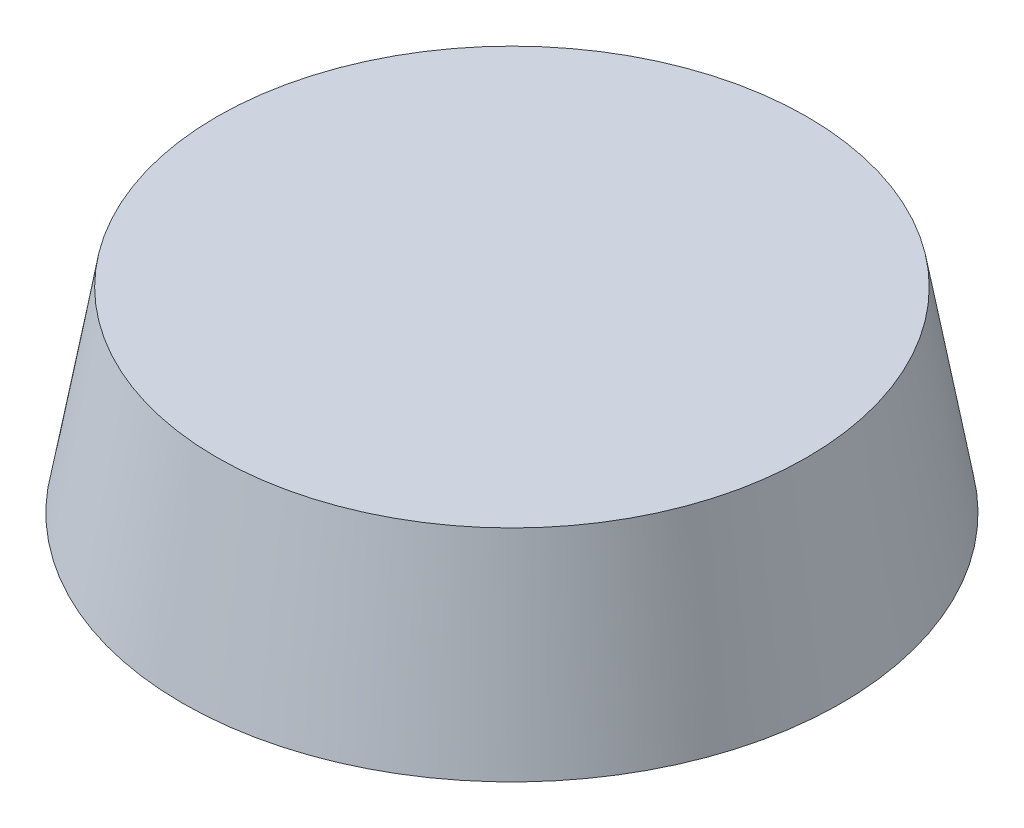
SolidWorks part; units mm, degrees
ref_plane "Front Plane" through (0, 0, 0) normal (0, 0, 1) x (1, 0, 0)
ref_plane "Top Plane" through (0, 0, 0) normal (0, 1, 0) x (1, 0, 0)
ref_plane "Right Plane" through (0, 0, 0) normal (1, 0, 0) x (0, 0, -1)
sketch "Sketch1" plane through (0, 0, 0) normal (0, 0, 1) x (1, 0, 0)
  line L0 (0, 62.1692) -> (0, -19.1974) construction
  line L1 (0, 7) -> (-10.7657, 7)
  line L2 (-10.7657, 7) -> (-12, 0)
  dimension "D1" = 7
  dimension "D2" = 100
  dimension "D3" = 12
revolve "Revolve-Thin1" add sketch "Sketch1" angle 360 about L0
ref_plane "Plane1" through (0, 0.0868, 0) normal (0, -1, 0) x (-1, 0, 0)
split "Split1" trim tools "Plane1" bodies to split 101 resulting bodies 103
